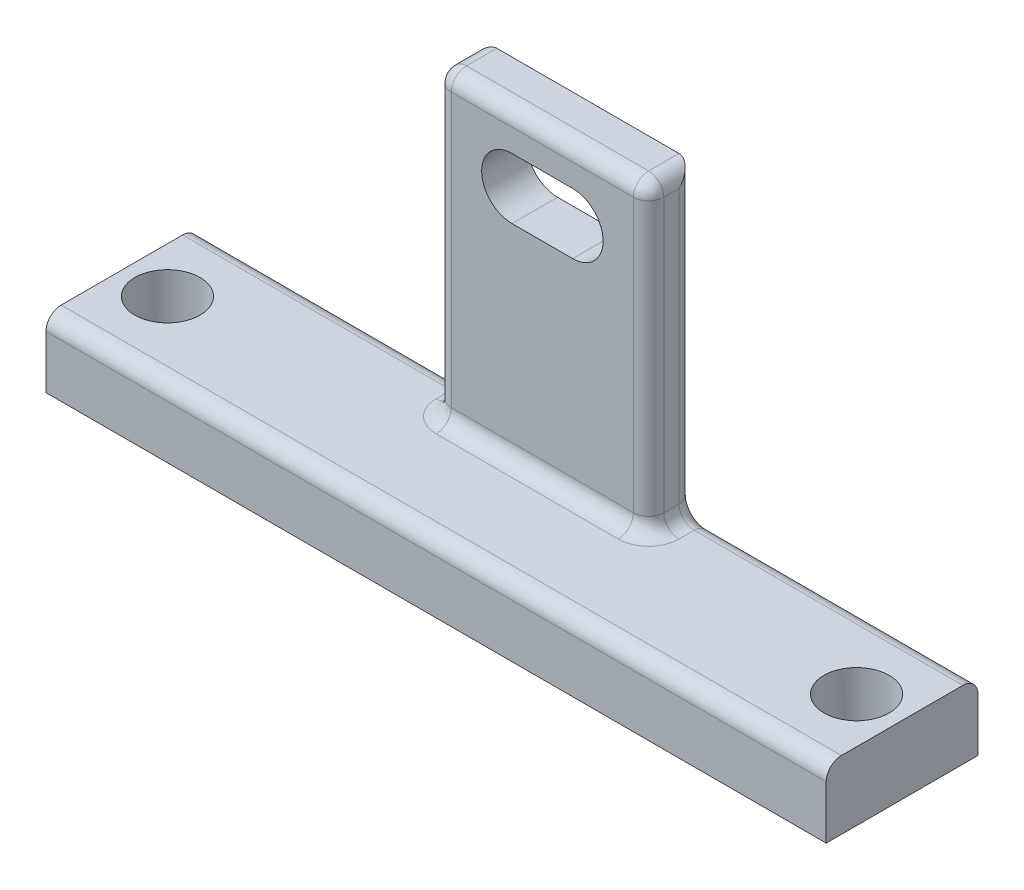
SolidWorks part; units mm, degrees
ref_plane "Front Plane" through (0, 0, 0) normal (0, 0, 1) x (1, 0, 0)
ref_plane "Top Plane" through (0, 0, 0) normal (0, 1, 0) x (1, 0, 0)
ref_plane "Right Plane" through (0, 0, 0) normal (1, 0, 0) x (0, 0, -1)
sketch "Sketch1" plane through (0, 0, 0) normal (0, 0, 1) x (1, 0, 0)
  line L1 (-6.4884, 3.6453) -> (44.9116, 3.6453)
  line L2 (-6.4884, 3.6453) -> (-6.4884, -0.8547)
  line L3 (-6.4884, -0.8547) -> (44.9116, -0.8547)
  line L4 (44.9116, 3.6453) -> (44.9116, -0.8547)
  dimension "D1" = 4.5
  dimension "D2" = 51.4
extrude "Boss-Extrude1" add sketch "Sketch1" along normal blind 10
sketch "Sketch2" plane through (0, 3.6453, 0) normal (0, 1, 0) x (1, 0, 0)
  line L0 (44.9116, 0) -> (-6.4884, 0) construction
  line L1 (-6.4884, -10) -> (-6.4884, 0) construction
  line L2 (44.9116, -10) -> (44.9116, 0) construction
  circle A0 centre (-3.4884, -5) radius 2.15
  circle A1 centre (41.9116, -5) radius 2.15
  dimension "D1" = 4.3
  dimension "D4" = 4.3
  dimension "D2" = 5
  dimension "D3" = 3
  dimension "D5" = 5
  dimension "D6" = 3
extrude "Cut-Extrude1" cut sketch "Sketch2" against normal through all both and the other way through all
sketch "Sketch3" plane through (0, 3.6453, 0) normal (0, 1, 0) x (1, 0, 0)
  line L0 (44.9116, 0) -> (-6.4884, 0) construction
  line L1 (12.2116, 0) -> (26.2116, 0)
  line L2 (12.2116, 0) -> (12.2116, -3)
  line L3 (12.2116, -3) -> (26.2116, -3)
  line L4 (26.2116, 0) -> (26.2116, -3)
  line L7 (-6.4884, -10) -> (-6.4884, 0) construction
  dimension "D1" = 3
  dimension "D2" = 14
  dimension "D3" = 18.7
extrude "Boss-Extrude2" add sketch "Sketch3" along normal blind 20
sketch "Sketch4" plane through (0, 0, 3) normal (0, 0, 1) x (1, 0, 0)
  line L0 (17.2116, 21.1453) -> (21.2116, 21.1453)
  line L1 (17.2116, 17.1453) -> (21.2116, 17.1453)
  line L2 (12.2116, 3.6453) -> (26.2116, 3.6453) construction
  line L3 (26.2116, 23.6453) -> (26.2116, 3.6453) construction
  arc A0 (21.2116, 21.1453) -> (21.2116, 17.1453) centre (21.2116, 19.1453) cw
  arc A1 (17.2116, 17.1453) -> (17.2116, 21.1453) centre (17.2116, 19.1453) cw
  dimension "D1" = 4
  dimension "D2" = 13.5
  dimension "D3" = 4
  dimension "D4" = 4
  dimension "D5" = 5
extrude "Cut-Extrude2" cut sketch "Sketch4" against normal blind 20
fillet "Fillet1" radius 1 13 edges at (26.2116, 13.6453, 0) (2.8616, 3.6453, 0) (12.2116, 13.6453, 0) (12.2116, 23.6453, 1.5) (12.2116, 13.6453, 3) (19.2116, 23.6453, 3) (26.2116, 13.6453, 3) (19.2116, 3.6453, 3) (35.5616, 3.6453, 0) (19.2116, 3.6453, 10) (26.2116, 23.6453, 1.5) (26.2116, 3.6453, 1.5) (12.2116, 3.6453, 1.5)
